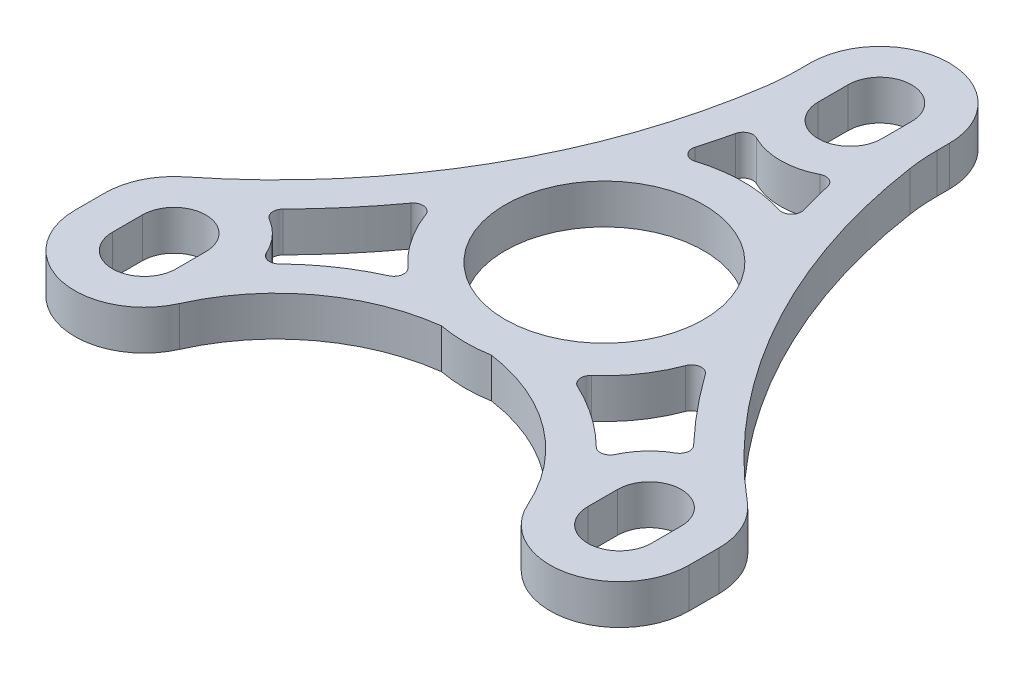
SolidWorks part; units mm, degrees
ref_plane "Front Plane" through (0, 0, 0) normal (0, 0, 1) x (1, 0, 0)
ref_plane "Top Plane" through (0, 0, 0) normal (0, 1, 0) x (1, 0, 0)
ref_plane "Right Plane" through (0, 0, 0) normal (1, 0, 0) x (0, 0, -1)
sketch "Sketch1" plane through (0, 0, 0) normal (0, 1, 0) x (1, 0, 0)
  line L0 (0, 0) -> (0, 13.11) construction
  line L1 (-12.0849, -10.32) -> (11.8351, -10.32) construction
  line L2 (0, 13.86) -> (0, 12.36) construction
  line L3 (1.6, 13.86) -> (1.6, 12.36)
  line L4 (-1.6, 13.86) -> (-1.6, 12.36)
  line L5 (11.8351, -9.57) -> (11.8351, -11.07) construction
  line L6 (13.4351, -9.57) -> (13.4351, -11.07)
  line L7 (10.2351, -9.57) -> (10.2351, -11.07)
  line L8 (-12.0849, -9.57) -> (-12.0849, -11.07) construction
  line L9 (-10.4849, -9.57) -> (-10.4849, -11.07)
  line L10 (-13.6849, -9.57) -> (-13.6849, -11.07)
  line L11 (-8.5849, -9.57) -> (-8.5849, -11.07)
  line L12 (-15.5849, -9.57) -> (-15.5849, -11.07)
  line L13 (3.5, 13.86) -> (3.5, 12.36)
  line L14 (-3.5, 13.86) -> (-3.5, 12.36)
  line L15 (15.3351, -9.57) -> (15.3351, -11.07)
  line L16 (8.3351, -9.57) -> (8.3351, -11.07)
  arc A1 (1.6, 13.86) -> (-1.6, 13.86) centre (0, 13.86) ccw
  arc A2 (-1.6, 12.36) -> (1.6, 12.36) centre (0, 12.36) ccw
  arc A3 (13.4351, -9.57) -> (10.2351, -9.57) centre (11.8351, -9.57) ccw
  arc A4 (10.2351, -11.07) -> (13.4351, -11.07) centre (11.8351, -11.07) ccw
  arc A5 (-10.4849, -9.57) -> (-13.6849, -9.57) centre (-12.0849, -9.57) ccw
  arc A6 (-13.6849, -11.07) -> (-10.4849, -11.07) centre (-12.0849, -11.07) ccw
  circle A7 centre (0, 0) radius 5
  circle A8 centre (0, 0) radius 2.5 construction
  arc A9 (-15.5849, -11.07) -> (-8.5849, -11.07) centre (-12.0849, -11.07) ccw
  arc A12 (3.5, 13.86) -> (-3.5, 13.86) centre (0, 13.86) ccw
  arc A13 (8.3351, -11.07) -> (15.3351, -11.07) centre (11.8351, -11.07) ccw
  arc A14 (15.3351, -9.57) -> (8.3351, -9.57) centre (11.8351, -9.57) ccw
  arc A16 (-3.5, 12.36) -> (3.5, 12.36) centre (0, 12.36) ccw
  arc A17 (-3.5, 12.36) -> (3.5, 12.36) centre (0, 12.36) ccw construction
  circle A18 centre (0, 0) radius 7
  arc A19 (-8.5849, -9.57) -> (-15.5849, -9.57) centre (-12.0849, -9.57) ccw
  arc A20 (-8.5849, -9.57) -> (-15.5849, -9.57) centre (-12.0849, -9.57) ccw construction
  arc A23 (15.3351, -9.57) -> (8.3351, -9.57) centre (11.8351, -9.57) ccw construction
  point P0 (0, 0)
  point P8 (0, 13.11)
  point P14 (11.8351, -10.32)
  point P21 (-12.0849, -10.32)
  point P47 (-7.67, -8.8807)
  point P48 (7.05, -9.1703)
  point P49 (-2.7296, 8.6574)
  point P51 (0, 0)
  point P55 (-4.6, 11.9913)
  dimension "D5" = 1.6
  dimension "D7" = 10
  dimension "D8" = 5
  dimension "D10" = 3.5
  dimension "D1" = 12.0849
  dimension "D2" = 23.92
  dimension "D3" = 13.11
  dimension "D4" = 23.43
  dimension "D6" = 1.5
  dimension "D12" = 2
extrude "Boss-Extrude1" add sketch "Sketch1" along normal blind 2
sketch "Sketch2" plane through (0, 2, 0) normal (0, 1, 0) x (1, 0, 0)
  line L3 (-8.8869, -12.4922) -> (-10.5315, -11.7608)
  line L4 (8.6371, -12.4922) -> (10.2818, -11.7608)
  line L6 (3.4774, 12.7571) -> (1.689, 12.5529)
  line L8 (14.0757, -6.8812) -> (12.9234, -8.264)
  line L9 (-13.1434, -8.2398) -> (-14.2642, -6.8313)
  line L10 (-1.69, 12.5444) -> (-3.4794, 12.7396)
  circle A2 centre (0, 0) radius 5 construction
  arc A5 (14.0757, -6.8812) -> (3.4774, 12.7571) centre (33.2754, 16.1594) cw
  arc A6 (-8.8869, -12.4922) -> (8.6371, -12.4922) centre (-0.1249, -16.3889) cw
  arc A7 (-15.5849, -11.07) -> (-8.5849, -11.07) centre (-12.0849, -11.07) ccw construction
  arc A8 (8.3351, -11.07) -> (15.3351, -11.07) centre (11.8351, -11.07) ccw construction
  arc A9 (-10.5315, -11.7608) -> (10.2818, -11.7608) centre (-0.1249, -16.3889) cw
  arc A12 (15.3351, -9.57) -> (8.3351, -9.57) centre (11.8351, -9.57) ccw construction
  arc A15 (-3.5, 12.36) -> (3.5, 12.36) centre (0, 12.36) ccw construction
  circle A17 centre (0, 0) radius 7 construction
  arc A18 (12.9234, -8.264) -> (1.689, 12.5529) centre (33.2754, 16.1594) cw
  arc A20 (-14.2642, -6.8313) -> (-3.4794, 12.7396) centre (-32.3437, 15.8887) ccw
  arc A21 (-8.5849, -9.57) -> (-15.5849, -9.57) centre (-12.0849, -9.57) ccw construction
  arc A22 (-13.1434, -8.2398) -> (-1.69, 12.5444) centre (-32.3437, 15.8887) ccw
  dimension "D1" = 1.8
  dimension "D2" = 1.8
  dimension "D3" = 1.8
extrude "Boss-Extrude2" add sketch "Sketch2" against normal up to surface (2 mm away) up to face at (0, 0, -13.11)
fillet "Fillet3" radius 0.5 12 edges at (10.7255, 1, 6.2506) (8.4104, 1, 8.8479) (-4.0613, 1, 5.7014) (3.9739, 1, 5.7626) (3.0513, 1, -6.3) (6.8379, 1, 1.4975) (-6.8473, 1, 1.454) (-3.0341, 1, -6.3082) (-2.1556, 1, -9.6026) (2.1656, 1, -9.6105) (-10.9051, 1, 6.2748) (-8.6602, 1, 8.8479)
fillet "Fillet4" radius 10 2 edges at (3.5, 1, -12.5647) (-3.5, 1, -12.5558)
